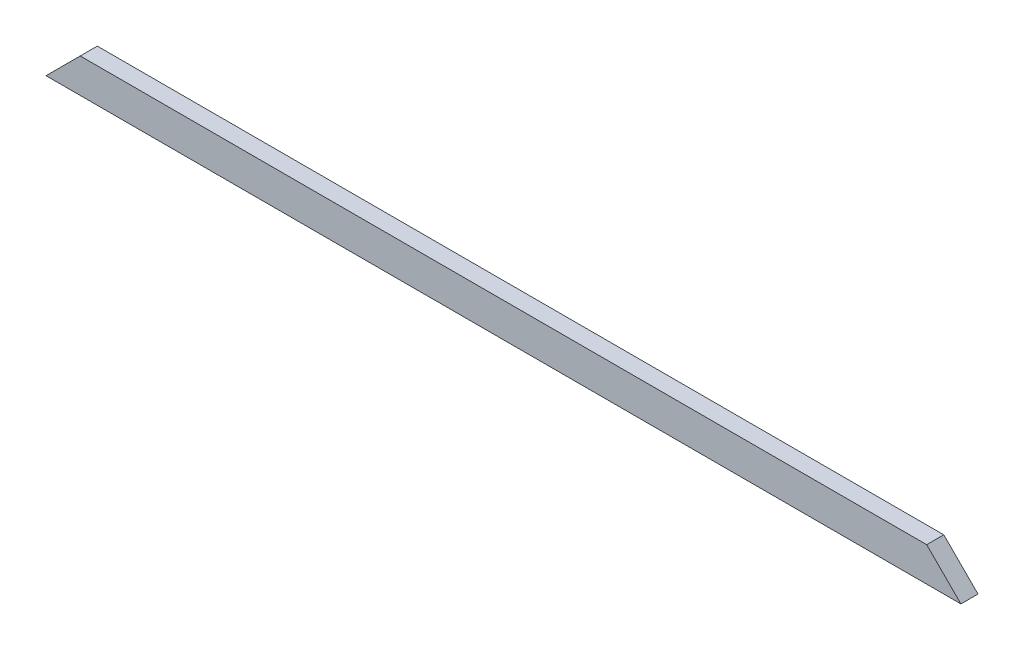
SolidWorks part; units mm, degrees
ref_plane "Front Plane" through (0, 0, 0) normal (0, 0, 1) x (1, 0, 0)
ref_plane "Top Plane" through (0, 0, 0) normal (0, 1, 0) x (1, 0, 0)
ref_plane "Right Plane" through (0, 0, 0) normal (1, 0, 0) x (0, 0, -1)
sketch "Sketch1" plane through (0, 0, 0) normal (0, 0, 1) x (1, 0, 0)
  line L0 (0, 0) -> (38.1, 38.1)
  line L1 (0, 0) -> (1019.175, 0)
  line L3 (38.1, 38.1) -> (981.075, 38.1)
  line L5 (1019.175, 0) -> (981.075, 38.1)
  dimension "D1" = 38.1
  dimension "D2" = 1019.175
  dimension "D3" = 45
  dimension "D4" = 45
extrude "Boss-Extrude1" add sketch "Sketch1" along normal blind 19.05
